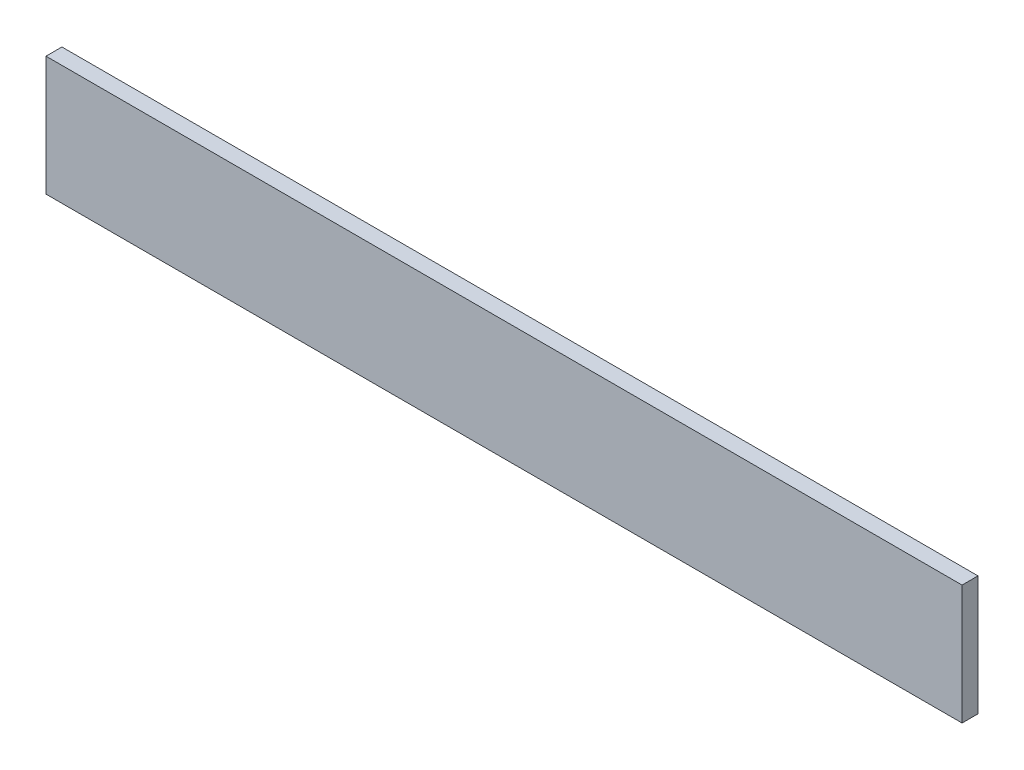
SolidWorks part; units mm, degrees
ref_plane "Front Plane" through (0, 0, 0) normal (0, 0, 1) x (1, 0, 0)
ref_plane "Top Plane" through (0, 0, 0) normal (0, 1, 0) x (1, 0, 0)
ref_plane "Right Plane" through (0, 0, 0) normal (1, 0, 0) x (0, 0, -1)
sketch "Sketch1" plane through (0, 0, 0) normal (0, 0, 1) x (1, 0, 0)
  line L0 (0, 0) -> (230, 0)
  line L1 (230, 0) -> (230, 30)
  line L2 (230, 30) -> (0, 30)
  line L3 (0, 0) -> (0, 30)
  dimension "D1" = 30
  dimension "D2" = 230
extrude "Boss-Extrude1" add sketch "Sketch1" along normal blind 4
